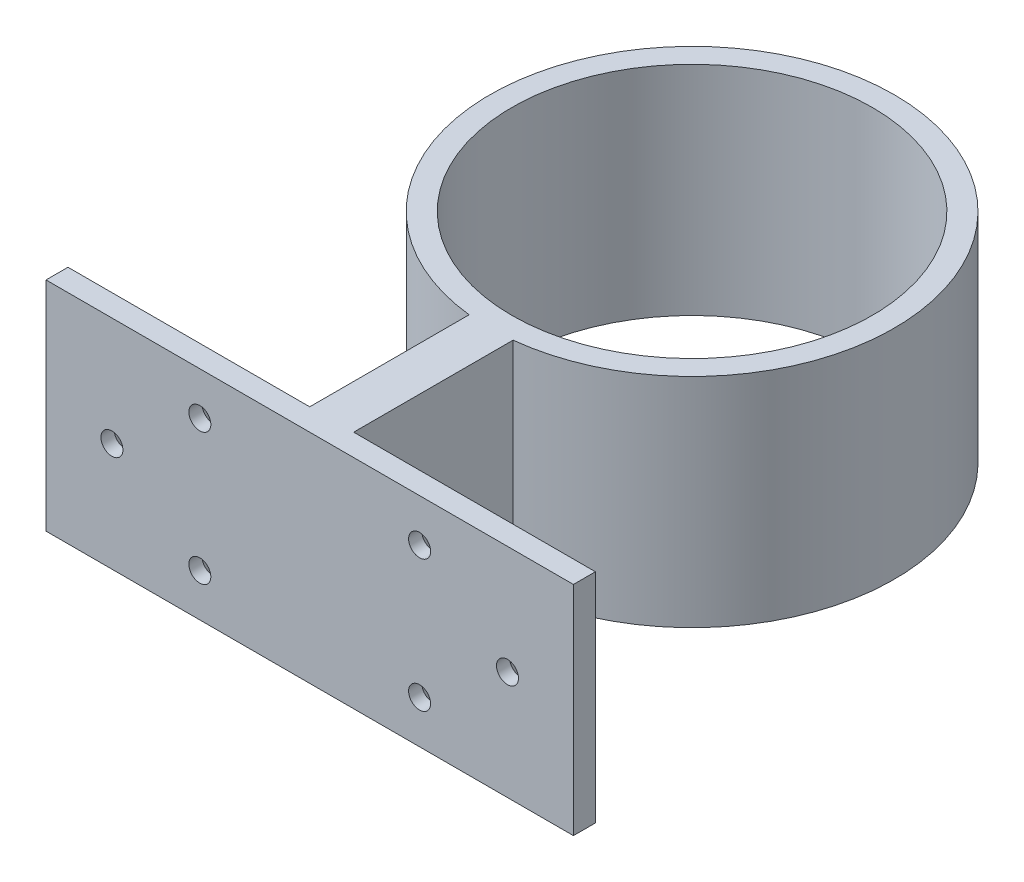
SolidWorks part; units mm, degrees
ref_plane "Front Plane" through (0, 0, 0) normal (0, 0, 1) x (1, 0, 0)
ref_plane "Top Plane" through (0, 0, 0) normal (0, 1, 0) x (1, 0, 0)
ref_plane "Right Plane" through (0, 0, 0) normal (1, 0, 0) x (0, 0, -1)
sketch "Sketch3" plane through (0, 0, 0) normal (0, 1, 0) x (1, 0, 0)
  line L1 (5, -82) -> (60, -82)
  line L2 (60, -82) -> (60, -87)
  line L3 (60, -87) -> (-60, -87)
  line L4 (-60, -87) -> (-60, -82)
  line L5 (-60, -82) -> (-5, -82)
  line L6 (-5, -45.7275) -> (-5, -82)
  line L7 (5, -45.7275) -> (5, -82)
  arc A0 (5, -45.7275) -> (-5, -45.7275) centre (0, 0) ccw
  circle A1 centre (0, 0) radius 41
  point P6 (0, 0)
  point P11 (0, 0)
  point P12 (0, 0)
  point P13 (0, 0)
  point P18 (0, 0)
  dimension "D1" = 92
  dimension "D2" = 82
  dimension "D3" = 5
  dimension "D4" = 60
  dimension "D6" = 87
  dimension "82" = 82
extrude "Boss-Extrude1" add sketch "Sketch3" along normal mid plane 49.5
sketch "Sketch4" plane through (0, 0, 87) normal (0, 0, 1) x (1, 0, 0)
  line L0 (0, 24.75) -> (0, -24.75)
  line L1 (-60, 24.75) -> (60, 24.75) construction
  line L2 (-60, -24.75) -> (60, -24.75) construction
  line L3 (60, 0) -> (-60, 0)
  line L4 (60, 24.75) -> (60, -24.75) construction
  line L5 (-60, 24.75) -> (-60, -24.75) construction
  line L6 (-25, 24.75) -> (-25, -24.75)
  line L7 (25, 24.75) -> (25, -24.75)
  line L8 (60, 15) -> (-60, 15)
  line L9 (60, -15) -> (-60, -15)
  circle A0 centre (-25, 15) radius 2.5
  circle A2 centre (-45, 0) radius 2.5
  circle A3 centre (-25, -15) radius 2.5
  circle A4 centre (25, -15) radius 2.5
  circle A5 centre (45, 0) radius 2.5
  circle A6 centre (25, 15) radius 2.5
  dimension "D5" = 5
  dimension "D6" = 45
  dimension "D1" = 25
  dimension "D2" = 25
  dimension "D3" = 15
  dimension "D4" = 15
extrude "Cut-Extrude1" cut sketch "Sketch4" against normal blind 30 contours A2 | A0 | A3 | A6 | A4 | A5
chamfer "Chamfer1" distance 2 angle 45 6 edges at (27.5, -15, 82) (47.5, 0, 82) (27.5, 15, 82) (-22.5, -15, 82) (-42.5, 0, 82) (-22.5, 15, 82)
